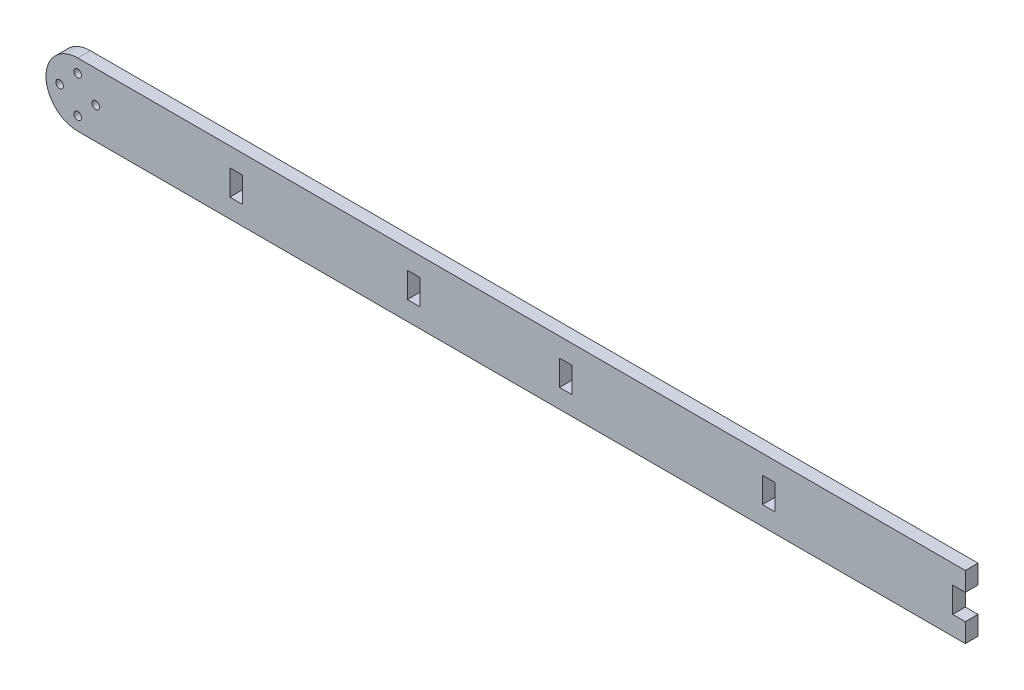
SolidWorks part; units mm, degrees
material "아크릴(내충격성)"
ref_plane "정면" through (0, 0, 0) normal (0, 0, 1) x (1, 0, 0)
ref_plane "윗면" through (0, 0, 0) normal (0, 1, 0) x (1, 0, 0)
ref_plane "우측면" through (0, 0, 0) normal (1, 0, 0) x (0, 0, -1)
sketch "스케치1" plane through (0, 0, 0) normal (0, 0, 1) x (1, 0, 0)
  line L0 (0, -12.5) -> (350, -12.5)
  line L1 (0, 12.5) -> (350, 12.5)
  line L2 (350, 12.5) -> (350, 5)
  line L3 (350, -5) -> (350, -12.5)
  line L4 (345, 5) -> (345, -5)
  line L6 (345, 5) -> (350, 5)
  line L7 (345, -5) -> (350, -5)
  arc A0 (0, 12.5) -> (0, -12.5) centre (0, 0) ccw
  circle A1 centre (7.1163, 0) radius 1.5
  circle A2 centre (-7.1163, 0) radius 1.5
  circle A3 centre (0, 7.25) radius 1.5
  circle A4 centre (0, -7.25) radius 1.5
  dimension "D1" = 25
  dimension "D2" = 350
extrude "보스-돌출1" add sketch "스케치1" along normal blind 5
sketch "스케치2" plane through (0, 0, 0) normal (0, 0, -1) x (-1, 0, 0)
  circle A0 centre (0, 0) radius 10
  dimension "D1" = 20
sketch "스케치3" plane through (0, 0, 0) normal (0, 0, -1) x (-1, 0, 0)
  line L1 (-15, 12.5) -> (-15, -12.5) construction
  line L2 (-350, 12.5) -> (0, 12.5) construction
  line L3 (0, -12.5) -> (-350, -12.5) construction
  line L6 (-315, 12.5) -> (-315, -12.5) construction
  line L7 (-275, 5) -> (-275, -5)
  line L8 (-275, 12.5) -> (-275, -12.5) construction
  line L9 (-270, 5) -> (-270, -5)
  line L10 (-270, -5) -> (-275, -5)
  line L11 (-270, 5) -> (-275, 5)
  line L12 (-195, 5) -> (-195, -5)
  line L13 (-135, 5) -> (-135, -5)
  line L14 (-190, 5) -> (-190, -5)
  line L15 (-190, -5) -> (-195, -5)
  line L16 (-190, 5) -> (-195, 5)
  line L17 (-65, 5) -> (-65, -5)
  line L18 (-135, -5) -> (-130, -5)
  line L19 (-130, -5) -> (-130, 5)
  line L20 (-130, 5) -> (-135, 5)
  line L21 (-65, -5) -> (-60, -5)
  line L22 (-60, -5) -> (-60, 5)
  line L23 (-60, 5) -> (-65, 5)
  line L24 (-195, 12.5) -> (-195, -12.5) construction
  line L25 (-135, 12.5) -> (-135, -12.5) construction
  line L26 (-65, 12.5) -> (-65, -12.5) construction
  dimension "D1" = 40
  dimension "D2" = 120
  dimension "D3" = 60
  dimension "D4" = 70
extrude "컷-돌출1" cut sketch "스케치3" against normal through all
